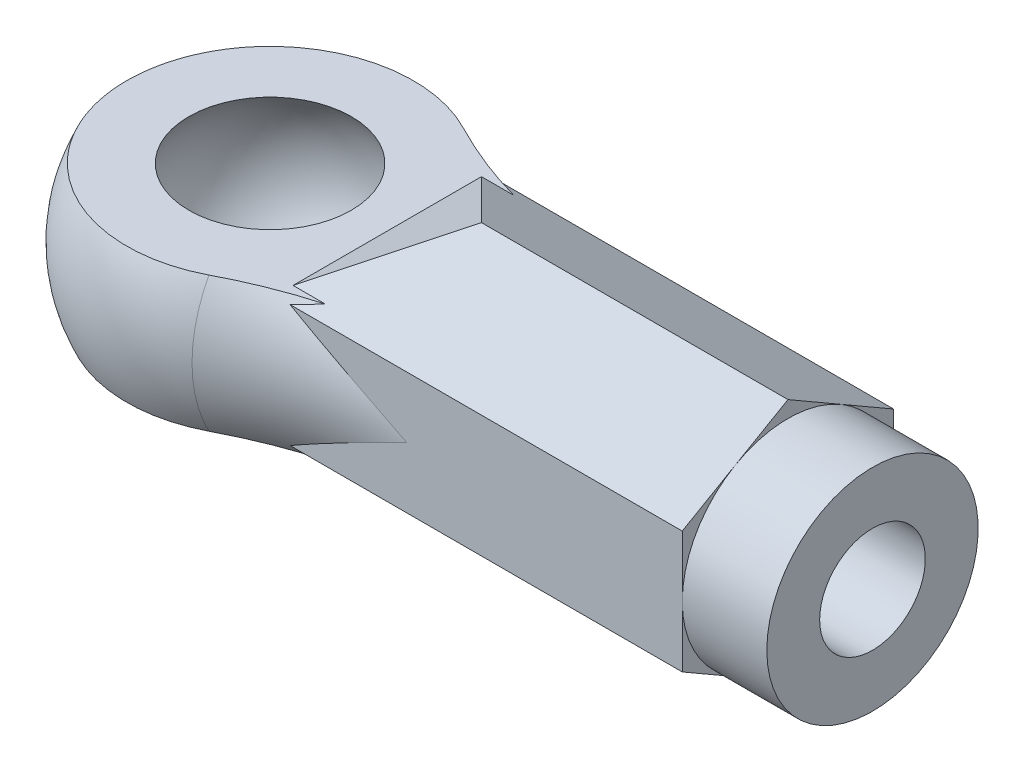
SolidWorks part; units mm, degrees
ref_plane "Plan de face" through (0, 0, 0) normal (0, 0, 1) x (1, 0, 0)
ref_plane "Plan de dessus" through (0, 0, 0) normal (0, 1, 0) x (1, 0, 0)
ref_plane "Plan de droite" through (0, 0, 0) normal (1, 0, 0) x (0, 0, -1)
sketch "Esquisse1" plane through (0, 0, 0) normal (0, 0, 1) x (1, 0, 0)
  line L0 (-2.5, 0) -> (-3.75, 0)
  line L1 (2.5, 0) -> (4.5, 0)
  line L2 (4.5, 0) -> (4.5, 1.25)
  line L3 (4.5, 1.25) -> (14.25, 1.25)
  line L4 (14.25, 1.25) -> (14.25, 2.5)
  line L5 (14.25, 2.5) -> (5.7282, 2.5)
  line L6 (4.5, 0) -> (14.25, 0) construction
  arc A0 (1.5622, 3.4091) -> (-3.75, 0) centre (0, 0) ccw
  arc A1 (2.5, 0) -> (-2.5, 0) centre (0, 0) ccw
  arc A2 (5.7282, 2.5) -> (1.5622, 3.4091) centre (5.7282, 12.5) cw
  dimension "D1" = 5
  dimension "D2" = 7.5
  dimension "D7" = 10
  dimension "D3" = 2.5
  dimension "D4" = 5
  dimension "D5" = 18
  dimension "D6" = 2
revolve "Révolution1" add sketch "Esquisse1" angle 360 about L6
sketch "Esquisse3" plane through (0, 0, 0) normal (0, 0, 1) x (1, 0, 0)
  line L0 (0, 0) -> (-3.75, 0) construction
  line L1 (-3.75, 4) -> (6, 4)
  line L2 (-3.75, 4) -> (-3.75, 1.6)
  line L3 (-3.75, 1.6) -> (6, 1.6)
  line L4 (6, 4) -> (6, 1.6)
  line L5 (6, -4) -> (6, -1.6)
  line L6 (-3.75, -1.6) -> (6, -1.6)
  line L7 (-3.75, -4) -> (-3.75, -1.6)
  line L8 (-3.75, -4) -> (6, -4)
  arc A1 (1.5622, 3.4091) -> (1.5622, -3.4091) centre (0, 0) ccw construction
  dimension "D1" = 8
  dimension "D2" = 3.2
  dimension "D3" = 6
extrude "Enlèv. mat.-Extru.1" cut sketch "Esquisse3" against normal mid plane 10
sketch "Esquisse2" plane through (14.25, 0, 0) normal (1, 0, 0) x (0, 0, -1)
  line L1 (0, 2.8868) -> (-2.5, 1.4434)
  line L2 (-2.5, 1.4434) -> (-2.5, -1.4434)
  line L3 (-2.5, -1.4434) -> (0, -2.8868)
  line L4 (0, -2.8868) -> (2.5, -1.4434)
  line L5 (2.5, -1.4434) -> (2.5, 1.4434)
  line L6 (2.5, 1.4434) -> (0, 2.8868)
  circle A0 centre (0, 0) radius 2.5 construction
  circle A1 centre (0, 0) radius 1.25 construction
  circle A2 centre (0, 0) radius 1.25
  circle A3 centre (0, 0) radius 2.5 construction
extrude "Boss.-Extru.1" add sketch "Esquisse2" against normal blind 10 from offset 2 offset against normal yes
sketch "Esquisse4" plane through (0, 0, 0) normal (0, 0, 1) x (1, 0, 0)
  line L0 (2.7713, 1.6) -> (5, 2.8868)
  line L1 (2.25, 2.8868) -> (12.25, 2.8868) construction
  line L2 (5, 2.8868) -> (-3.75, 2.8868)
  line L3 (-3.75, 2.8868) -> (-3.75, 1.6)
  line L4 (0, 0) -> (14.25, 0) construction
  line L5 (14.25, -2.5) -> (14.25, 2.5) construction
  line L6 (-3.75, -1.6) -> (2.7713, -1.6)
  line L7 (-3.75, -2.8868) -> (-3.75, -1.6)
  line L8 (-3.75, 1.6) -> (2.7713, 1.6)
  line L9 (1.5622, 1.6) -> (-3.3915, 1.6) construction
  line L10 (5, -2.8868) -> (-3.75, -2.8868)
  line L11 (2.7713, -1.6) -> (5, -2.8868)
  arc A0 (-3.3915, 1.6) -> (-3.3915, -1.6) centre (0, 0) ccw construction
  dimension "D1" = 150
extrude "Enlèv. mat.-Extru.2" cut sketch "Esquisse4" against normal mid plane 10
